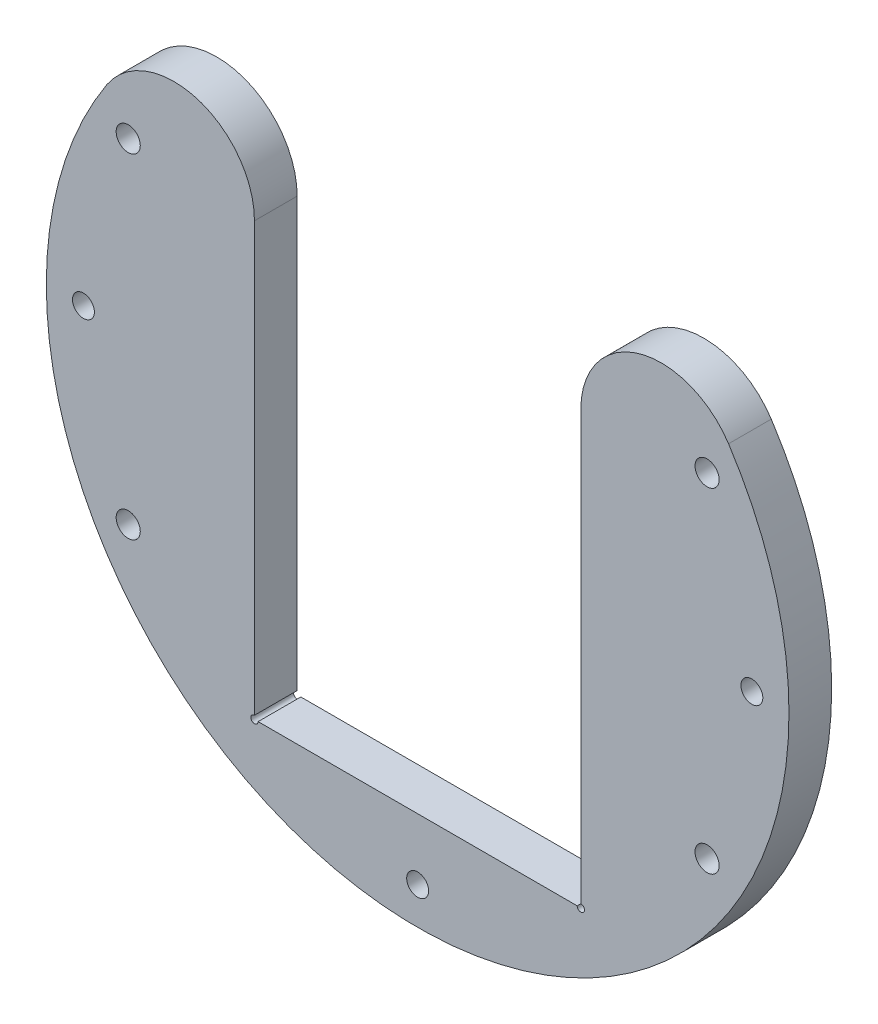
SolidWorks part; units mm, degrees
material "Acrylic (Medium-high impact)"
ref_plane "Front Plane" through (0, 0, 0) normal (0, 0, 1) x (1, 0, 0)
ref_plane "Top Plane" through (0, 0, 0) normal (0, 1, 0) x (1, 0, 0)
ref_plane "Right Plane" through (0, 0, 0) normal (1, 0, 0) x (0, 0, -1)
sketch "Sketch1" plane through (0, 0, 0) normal (0, 0, 1) x (1, 0, 0)
  line L0 (0, 0) -> (0, 76.2) construction
  line L3 (-22.325, 28.496) -> (22.325, 28.496) construction
  line L4 (22.325, -37.323) -> (22.325, 28.496)
  line L5 (0, 76.2) -> (0, -50.8) construction
  line L6 (-50.8, 0) -> (50.8, 0) construction
  line L7 (-22.325, -37.323) -> (22.325, -37.323)
  line L8 (-22.325, -37.323) -> (-22.325, 28.496)
  line L9 (-22.325, 28.496) -> (-22.325, 45.6315)
  line L10 (22.325, 28.496) -> (22.325, 45.6315)
  line L11 (0, 0) -> (-45.72, 0) construction
  arc A0 (-22.325, 45.6315) -> (22.325, 45.6315) centre (0, 0) ccw
  circle A1 centre (-45.72, 0) radius 1.5
  circle A2 centre (0, 45.72) radius 1.5 [skipped]
  circle A3 centre (45.72, 0) radius 1.5
  circle A4 centre (0, -45.72) radius 1.5
  circle A5 centre (0, 45.72) radius 1.65 construction
  circle A6 centre (39.5947, 22.86) radius 1.65
  circle A7 centre (39.5947, -22.86) radius 1.65
  circle A8 centre (0, -45.72) radius 1.65 construction
  circle A9 centre (-39.5947, -22.86) radius 1.65
  circle A10 centre (-39.5947, 22.86) radius 1.65
  point P13 (0, -37.323)
  point P27 (0, 0)
  point P38 (0, 0)
  dimension "D1" = 101.6
  dimension "D3" = 45.72
  dimension "D5" = 3
  dimension "D6" = 45.72
  dimension "D7" = 3.3
  dimension "D2" = 44.65
  dimension "D9" = 37.323
  dimension "D4" = 4
  dimension "D8" = 6
extrude "Boss-Extrude1" add sketch "Sketch1" along normal blind 5.842 contours A0 L7 L8 L3 L4
fillet "Fillet2" radius 11 2 edges at (22.325, 45.6315, 2.921) (-22.325, 45.6315, 2.921)
sketch "Sketch2" plane through (0, 0, 5.842) normal (0, 0, 1) x (1, 0, 0)
  circle A0 centre (-22.325, -37.323) radius 0.5
  circle A1 centre (22.325, -37.323) radius 0.5
  dimension "D1" = 1
extrude "Cut-Extrude1" cut sketch "Sketch2" against normal through all
